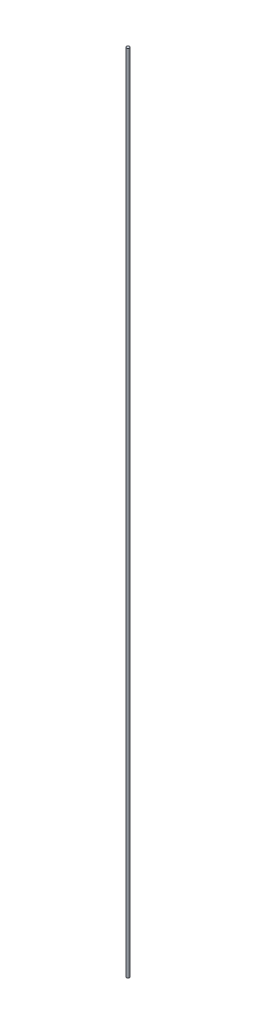
SolidWorks part; units mm, degrees
ref_plane "Front Plane" through (0, 0, 0) normal (0, 0, 1) x (1, 0, 0)
ref_plane "Top Plane" through (0, 0, 0) normal (0, 1, 0) x (1, 0, 0)
ref_plane "Right Plane" through (0, 0, 0) normal (1, 0, 0) x (0, 0, -1)
sketch "Sketch1" plane through (0, 0, 0) normal (0, 1, 0) x (1, 0, 0)
  circle A0 centre (0, 0) radius 12.7
  dimension "D1" = 25.4
extrude "Boss-Extrude3" add sketch "Sketch1" along normal blind 6852.5365
equation "\"E\"= 11.45 * 10 ^ 6"
equation "\"A\"= ( pi * 1 ^ 2 ) / 4"
equation "\"D\"= 1"
equation "\"def\"= 0.009"
equation "\"P\"= 300"
equation "\"L\"= ( \"def\" * \"A\" * \"E\" ) / \"P\""
